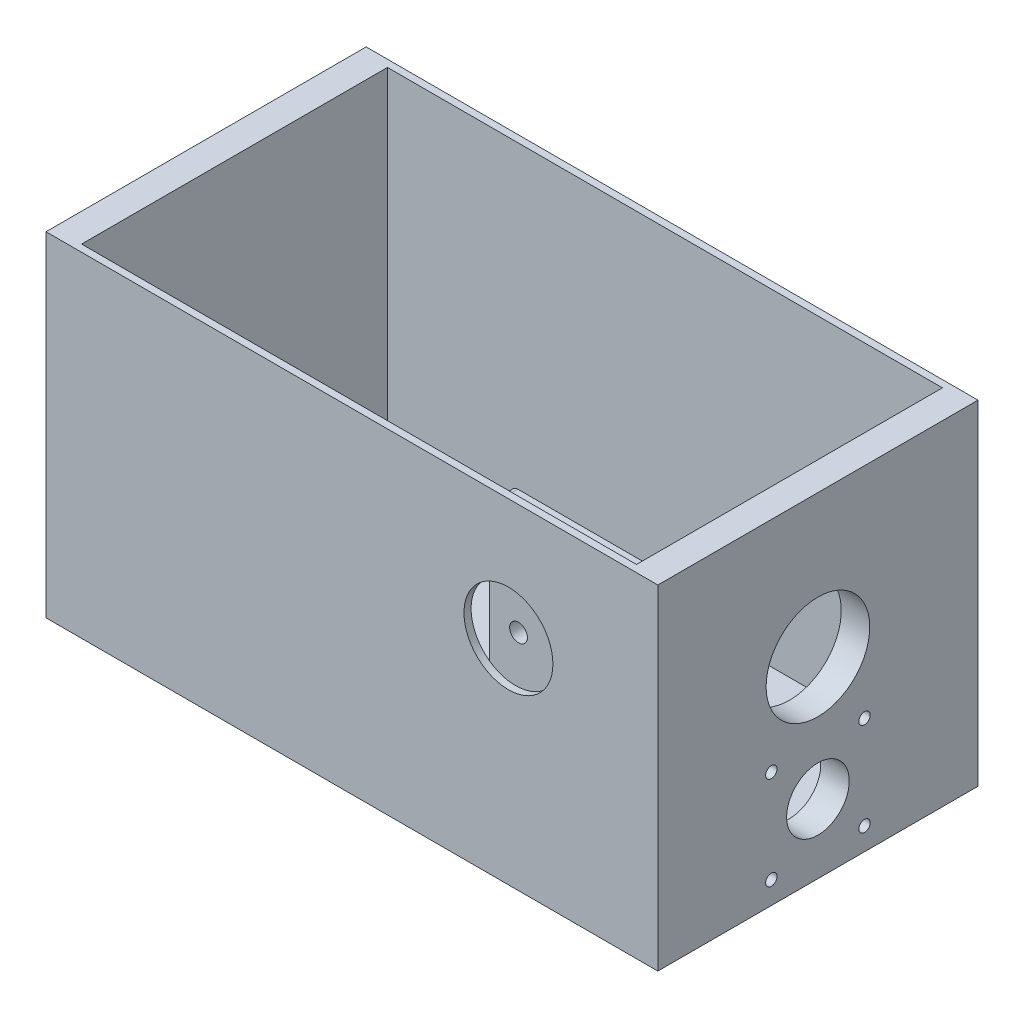
SolidWorks part; units mm, degrees
ref_plane "Front Plane" through (0, 0, 0) normal (0, 0, 1) x (1, 0, 0)
ref_plane "Top Plane" through (0, 0, 0) normal (0, 1, 0) x (1, 0, 0)
ref_plane "Right Plane" through (0, 0, 0) normal (1, 0, 0) x (0, 0, -1)
sketch "Sketch1" plane through (0, 0, 0) normal (0, 1, 0) x (1, 0, 0)
  line L1 (-101.6, -57.15) -> (101.6, -57.15)
  line L2 (-101.6, -57.15) -> (-101.6, 57.15)
  line L3 (-101.6, 57.15) -> (101.6, 57.15)
  line L4 (101.6, -57.15) -> (101.6, 57.15)
  line L5 (-101.6, -57.15) -> (101.6, 57.15) construction
  line L6 (-101.6, 57.15) -> (101.6, -57.15) construction
  point P0 (0, 0)
  dimension "10" = 203.2
  dimension "D2" = 114.3
extrude "Boss-Extrude1" add sketch "Sketch1" along normal blind 119.38
shell "Shell1" thickness 2.54
sketch "Sketch2" plane through (99.06, 0, 0) normal (-1, 0, 0) x (0, 0, 1)
  line L0 (22.225, 46.863) -> (-22.225, 46.863) construction
  line L5 (-22.225, 46.863) -> (-22.225, 2.413) construction
  line L10 (-22.225, 2.413) -> (22.225, 46.863) construction
  line L11 (-22.225, 46.863) -> (22.225, 2.413) construction
  line L12 (22.225, 46.863) -> (22.225, 2.413) construction
  line L14 (22.225, 2.413) -> (-22.225, 2.413) construction
  line L16 (0, 17.0459) -> (0, 33.3047) construction
  line L17 (1.822, 24.638) -> (-4.4847, 24.638) construction
  circle A0 centre (0, 68.58) radius 18.5
  circle A1 centre (16.637, 41.275) radius 2.032
  circle A5 centre (16.637, 8.001) radius 2.032
  circle A6 centre (-16.637, 8.001) radius 2.032
  circle A7 centre (-16.637, 41.275) radius 2.032
  circle A8 centre (0, 24.638) radius 11.176
  point P4 (0, 24.638)
  dimension "D3" = 37
  dimension "D4" = 4.064
  dimension "D5" = 33.274
  dimension "D6" = 22.352
  dimension "D1" = 44.45
  dimension "D2" = 44.45
extrude "Cut-Extrude1" cut sketch "Sketch2" against normal blind 2.54
sketch "Sketch3" plane through (101.6, 0, 0) normal (1, 0, 0) x (0, 0, -1)
  line L4 (-57.15, 0) -> (57.15, 0)
  line L5 (57.15, 0) -> (57.15, 119.38)
  line L6 (57.15, 119.38) -> (-57.15, 119.38)
  line L7 (-57.15, 119.38) -> (-57.15, 0)
  line L8 (-57.15, 0) -> (57.15, 0)
  line L9 (57.15, 0) -> (57.15, 119.38)
  line L10 (57.15, 119.38) -> (-57.15, 119.38)
  line L11 (-57.15, 119.38) -> (-57.15, 0)
  circle A0 centre (0, 68.58) radius 18.5 construction
  circle A1 centre (0, 68.58) radius 18.5
  circle A2 centre (-16.637, 8.001) radius 2.032 construction
  circle A3 centre (16.637, 8.001) radius 2.032 construction
  circle A4 centre (16.637, 41.275) radius 2.032 construction
  circle A5 centre (-16.637, 41.275) radius 2.032 construction
  circle A6 centre (-16.637, 8.001) radius 2.032
  circle A7 centre (16.637, 8.001) radius 2.032
  circle A8 centre (16.637, 41.275) radius 2.032
  circle A9 centre (-16.637, 41.275) radius 2.032
  circle A10 centre (0, 24.638) radius 11.176 construction
  circle A11 centre (0, 24.638) radius 11.176
  dimension "D1" = 0
extrude "Boss-Extrude3" add sketch "Sketch3" along normal blind 7.62
sketch "Sketch4" plane through (0, 0, 57.15) normal (0, 0, 1) x (1, 0, 0)
  line L1 (-101.6, 0) -> (109.22, 0) construction
  line L2 (109.22, 119.38) -> (109.22, 0) construction
  circle A0 centre (55.88, 76.2) radius 15.875
  dimension "D1" = 31.75
  dimension "D2" = 53.34
  dimension "D3" = 76.2
sketch "Sketch5" plane through (0, 2.54, 0) normal (0, 1, 0) x (1, 0, 0)
  line L5 (30.53, -38.55) -> (81.23, -38.55)
  line L6 (30.53, -38.55) -> (30.53, -30.93)
  line L7 (30.53, -30.93) -> (81.23, -30.93)
  line L8 (81.23, -38.55) -> (81.23, -30.93)
  line L9 (74.88, -38.55) -> (74.88, -39.95) construction
  dimension "D1" = 7.62
  dimension "D2" = 6.35
  dimension "D3" = 6.35
extrude "Cut-Extrude2" cut sketch "Sketch4" against normal blind 2.54
extrude "Boss-Extrude4" add sketch "Sketch5" along normal blind 95.25
sketch "Sketch6" plane through (0, 0, 38.55) normal (0, 0, 1) x (1, 0, 0)
  circle A1 centre (40.88, 91.2) radius 3.175
  circle A3 centre (70.88, 61.2) radius 3.175
  circle A4 centre (40.88, 61.2) radius 3.175
  circle A7 centre (70.88, 91.2) radius 3.175
  dimension "D1" = 6.35
  dimension "D2" = 6.35
  dimension "D3" = 6.35
  dimension "D4" = 6.35
extrude "Cut-Extrude3" cut sketch "Sketch6" against normal up to next
fillet "Fillet1" radius 2.54 2 edges at (30.53, 97.79, 34.74) (81.23, 97.79, 34.74)
fillet "Fillet2" radius 2.54 4 edges at (55.88, 2.54, 38.55) (81.23, 2.54, 34.74) (30.53, 2.54, 34.74) (55.88, 2.54, 30.93)
sketch "Sketch7" plane through (-101.6, 0, 0) normal (-1, 0, 0) x (0, 0, 1)
  line L4 (-57.15, 0) -> (57.15, 0)
  line L5 (57.15, 0) -> (57.15, 119.38)
  line L6 (57.15, 119.38) -> (-57.15, 119.38)
  line L7 (-57.15, 119.38) -> (-57.15, 0)
  line L8 (-57.15, 0) -> (57.15, 0)
  line L9 (57.15, 0) -> (57.15, 119.38)
  line L10 (57.15, 119.38) -> (-57.15, 119.38)
  line L11 (-57.15, 119.38) -> (-57.15, 0)
  dimension "D1" = 0
extrude "Boss-Extrude5" add sketch "Sketch7" along normal blind 7.62
sketch "Sketch8" plane through (0, 2.54, 0) normal (0, 1, 0) x (1, 0, 0)
  circle A2 centre (57.7271, -23.7315) radius 2.54
  circle A3 centre (59.4071, 34.2332) radius 2.54
  circle A4 centre (-26.4879, 34.2332) radius 2.54
  circle A5 centre (-28.2729, -23.7315) radius 2.54
  circle A6 centre (57.7271, -23.7315) radius 1.27
  circle A7 centre (59.4071, 34.2332) radius 1.27
  circle A8 centre (-26.4879, 34.2332) radius 1.27
  circle A9 centre (-28.2729, -23.7315) radius 1.27
  dimension "D1" = 5.08
  dimension "D2" = 5.08
  dimension "D3" = 5.08
  dimension "D4" = 5.08
  dimension "D5" = 2.54
  dimension "D6" = 2.54
  dimension "D7" = 2.54
  dimension "D8" = 2.54
extrude "Boss-Extrude6" add sketch "Sketch8" along normal blind 5.08
sketch "Sketch9" plane through (0, 0, -57.15) normal (0, 0, -1) x (-1, 0, 0)
  line L0 (-61.6571, 9.445) -> (-53.1571, 9.445) construction
  line L5 (-53.1571, 9.445) -> (-53.1571, 19.945) construction
  line L6 (-53.1571, 19.945) -> (-61.6571, 19.945) construction
  line L7 (-61.6571, 19.945) -> (-61.6571, 9.445) construction
  line L8 (-61.6571, 9.445) -> (-53.1571, 9.445) construction
  line L9 (-53.1571, 9.445) -> (-53.1571, 19.945) construction
  line L10 (-53.1571, 19.945) -> (-61.6571, 19.945) construction
  line L11 (-61.6571, 19.945) -> (-61.6571, 9.445) construction
  line L12 (-47.3071, 27.3712) -> (-32.0071, 27.3712)
  line L13 (-27.3571, 24.065) -> (-27.3571, 11.045) construction
  line L14 (-26.7571, 24.665) -> (-14.8571, 24.665) construction
  line L15 (-14.2571, 24.065) -> (-14.2571, 11.045) construction
  line L16 (-14.8571, 10.445) -> (-26.7571, 10.445) construction
  line L17 (-9.7571, 24.665) -> (2.1429, 24.665) construction
  line L18 (2.7429, 24.065) -> (2.7429, 11.045) construction
  line L19 (2.1429, 10.445) -> (-9.7571, 10.445) construction
  line L20 (-10.3571, 11.045) -> (-10.3571, 24.065) construction
  line L21 (-48.1071, 26.5712) -> (-48.1071, 10.1681)
  line L22 (-31.2134, 26.6712) -> (-31.2134, 10.107)
  line L23 (-47.8071, 9.8681) -> (-31.5071, 9.8681) construction
  line L24 (-47.8071, 9.8681) -> (-31.5071, 9.8681)
  line L25 (10.9129, 9.545) -> (15.9729, 9.545) construction
  line L26 (-62.6731, 8.429) -> (-52.1411, 8.429)
  line L27 (-52.1411, 8.429) -> (-52.1411, 20.961)
  line L28 (28.5729, 9.3212) -> (28.5729, 9.4912)
  line L29 (28.5729, 9.4912) -> (25.955, 9.4912)
  line L30 (25.7924, 9.5586) -> (25.1302, 10.2207)
  line L31 (25.0629, 10.3833) -> (25.0629, 11.2712)
  line L32 (25.2929, 11.5012) -> (31.8929, 11.5012)
  line L33 (32.1229, 11.2712) -> (32.1228, 10.3833)
  line L34 (32.0555, 10.2207) -> (31.3934, 9.5586)
  line L35 (31.2307, 9.4912) -> (28.6129, 9.4912)
  line L36 (28.6129, 9.4912) -> (28.6129, 9.3212)
  line L37 (28.6129, 9.3212) -> (31.2307, 9.3212)
  line L38 (31.5136, 9.4384) -> (32.1757, 10.1005)
  line L39 (32.2929, 10.3833) -> (32.2929, 11.2712)
  line L40 (31.8929, 11.6712) -> (25.2929, 11.6712)
  line L41 (24.8929, 11.2712) -> (24.8929, 10.3833)
  line L42 (25.01, 10.1005) -> (25.6721, 9.4384)
  line L43 (25.955, 9.3212) -> (28.5729, 9.3212)
  line L53 (28.6129, 9.3212) -> (31.2307, 9.3212) construction
  line L54 (31.5136, 9.4384) -> (32.1757, 10.1005) construction
  line L55 (32.2929, 10.3833) -> (32.2929, 11.2712) construction
  line L56 (31.8929, 11.6712) -> (25.2929, 11.6712) construction
  line L57 (24.8929, 11.2712) -> (24.8929, 10.3833) construction
  line L58 (25.01, 10.1005) -> (25.6721, 9.4384) construction
  line L59 (25.955, 9.3212) -> (28.5729, 9.3212) construction
  line L60 (-52.1411, 20.961) -> (-62.6731, 20.961)
  line L61 (-62.6731, 20.961) -> (-62.6731, 8.429)
  line L66 (-28.3731, 24.065) -> (-28.3731, 11.045)
  line L67 (-14.8571, 9.429) -> (-26.7571, 9.429)
  line L68 (6.9929, 12.5952) -> (6.9929, 14.885)
  line L69 (6.9929, 14.885) -> (6.9929, 16.885)
  line L70 (6.9929, 16.885) -> (6.9929, 20.265)
  line L71 (7.2428, 20.515) -> (19.6429, 20.515)
  line L72 (19.8928, 20.265) -> (19.8929, 16.885)
  line L73 (19.8929, 16.885) -> (19.8929, 14.8862)
  line L74 (19.8929, 14.8862) -> (19.8929, 12.5952)
  line L75 (19.8761, 12.505) -> (20.5929, 12.505)
  line L76 (20.5929, 12.505) -> (20.5929, 10.155)
  line L77 (20.5929, 10.155) -> (15.9729, 10.155)
  line L78 (15.9729, 10.155) -> (15.9729, 9.545)
  line L79 (15.9729, 9.545) -> (20.5429, 9.545)
  line L80 (20.5429, 9.545) -> (21.2928, 9.545)
  line L81 (21.2928, 9.545) -> (21.2929, 22.595)
  line L82 (21.2929, 22.595) -> (21.2929, 22.645)
  line L83 (21.2929, 22.645) -> (5.7929, 22.645)
  line L84 (5.7929, 22.645) -> (5.7929, 22.595)
  line L85 (5.7929, 22.595) -> (5.7929, 9.545)
  line L86 (5.7929, 9.545) -> (6.5429, 9.545)
  line L87 (6.5429, 9.545) -> (10.9129, 9.545)
  line L88 (10.9129, 9.545) -> (10.9129, 10.155)
  line L89 (10.9129, 10.155) -> (6.3929, 10.155)
  line L90 (6.3929, 10.155) -> (6.3929, 12.505)
  line L91 (6.3929, 12.505) -> (7.0096, 12.505)
  line L103 (15.9729, 9.545) -> (20.5429, 9.545) construction
  line L104 (20.5429, 9.545) -> (21.2928, 9.545) construction
  line L105 (21.2928, 9.545) -> (21.2929, 22.595) construction
  line L106 (21.2929, 22.595) -> (21.2929, 22.645) construction
  line L107 (21.2929, 22.645) -> (5.7929, 22.645) construction
  line L108 (5.7929, 22.645) -> (5.7929, 22.595) construction
  line L109 (5.7929, 22.595) -> (5.7929, 9.545) construction
  line L110 (5.7929, 9.545) -> (6.5429, 9.545) construction
  line L111 (6.5429, 9.545) -> (10.9129, 9.545) construction
  line L116 (-13.2411, 24.065) -> (-13.2411, 11.045)
  line L117 (-26.7571, 25.681) -> (-14.8571, 25.681)
  line L118 (-9.7571, 25.681) -> (2.1429, 25.681)
  line L119 (3.7589, 24.065) -> (3.7589, 11.045)
  line L120 (2.1429, 9.429) -> (-9.7571, 9.429)
  line L121 (-11.3731, 11.045) -> (-11.3731, 24.065)
  line L122 (10.9129, 8.529) -> (15.9729, 8.529)
  line L123 (15.9729, 8.529) -> (20.5429, 8.529)
  line L124 (20.5429, 8.529) -> (22.3088, 8.529)
  line L125 (22.3088, 8.529) -> (22.3089, 22.595)
  line L126 (22.3089, 22.595) -> (22.3089, 23.661)
  line L127 (22.3089, 23.661) -> (4.7769, 23.661)
  line L128 (4.7769, 23.661) -> (4.7769, 22.595)
  line L129 (4.7769, 22.595) -> (4.7769, 8.529)
  line L130 (4.7769, 8.529) -> (6.5429, 8.529)
  line L131 (6.5429, 8.529) -> (10.9129, 8.529)
  line L132 (28.6129, 8.3052) -> (31.2307, 8.3052)
  line L133 (32.232, 8.7199) -> (32.8941, 9.3821)
  line L134 (33.3089, 10.3833) -> (33.3089, 11.2712)
  line L135 (31.8929, 12.6872) -> (25.2929, 12.6872)
  line L136 (23.8769, 11.2712) -> (23.8769, 10.3833)
  line L137 (24.2916, 9.3821) -> (24.9537, 8.7199)
  line L138 (25.955, 8.3052) -> (28.5729, 8.3052)
  line L139 (-47.0911, 26.3552) -> (-32.2294, 26.3552) construction
  line L140 (-47.0911, 26.3552) -> (-47.0911, 10.8841) construction
  line L141 (-32.2294, 26.3552) -> (-32.2294, 10.107) construction
  line L142 (-47.0911, 10.8841) -> (-31.928, 10.8841) construction
  arc A1 (-47.3071, 27.3712) -> (-48.1071, 26.5712) centre (-47.3071, 26.5712) ccw construction
  arc A2 (6.9929, 12.5952) -> (7.0096, 12.505) centre (7.2437, 12.5952) ccw
  arc A3 (7.2428, 20.515) -> (6.9929, 20.265) centre (7.2428, 20.265) ccw
  arc A4 (19.8928, 20.265) -> (19.6429, 20.515) centre (19.6429, 20.265) ccw
  arc A5 (19.8761, 12.505) -> (19.8929, 12.5952) centre (19.642, 12.5952) ccw
  arc A10 (-31.2134, 26.6712) -> (-32.0071, 27.3712) centre (-32.0071, 26.5712) ccw construction
  arc A11 (-26.7571, 24.665) -> (-27.3571, 24.065) centre (-26.7571, 24.065) ccw construction
  arc A12 (25.7924, 9.5586) -> (25.955, 9.4912) centre (25.955, 9.7212) ccw
  arc A13 (25.0629, 10.3833) -> (25.1302, 10.2207) centre (25.2929, 10.3833) ccw
  arc A14 (25.2929, 11.5012) -> (25.0629, 11.2712) centre (25.2929, 11.2712) ccw
  arc A15 (32.1229, 11.2712) -> (31.8929, 11.5012) centre (31.8929, 11.2712) ccw
  arc A16 (32.0555, 10.2207) -> (32.1228, 10.3833) centre (31.8929, 10.3833) ccw
  arc A17 (31.2307, 9.4912) -> (31.3934, 9.5586) centre (31.2307, 9.7212) ccw
  arc A18 (31.2307, 9.3212) -> (31.5136, 9.4384) centre (31.2307, 9.7212) ccw
  arc A19 (32.1757, 10.1005) -> (32.2929, 10.3833) centre (31.8929, 10.3833) ccw
  arc A20 (32.2929, 11.2712) -> (31.8929, 11.6712) centre (31.8929, 11.2712) ccw
  arc A21 (25.2929, 11.6712) -> (24.8929, 11.2712) centre (25.2929, 11.2712) ccw
  arc A22 (24.8929, 10.3833) -> (25.01, 10.1005) centre (25.2929, 10.3833) ccw
  arc A23 (25.6721, 9.4384) -> (25.955, 9.3212) centre (25.955, 9.7212) ccw
  arc A30 (31.2307, 9.3212) -> (31.5136, 9.4384) centre (31.2307, 9.7212) ccw construction
  arc A31 (32.1757, 10.1005) -> (32.2929, 10.3833) centre (31.8929, 10.3833) ccw construction
  arc A32 (32.2929, 11.2712) -> (31.8929, 11.6712) centre (31.8929, 11.2712) ccw construction
  arc A33 (25.2929, 11.6712) -> (24.8929, 11.2712) centre (25.2929, 11.2712) ccw construction
  arc A34 (24.8929, 10.3833) -> (25.01, 10.1005) centre (25.2929, 10.3833) ccw construction
  arc A35 (25.6721, 9.4384) -> (25.955, 9.3212) centre (25.955, 9.7212) ccw construction
  arc A36 (-27.3571, 11.045) -> (-26.7571, 10.445) centre (-26.7571, 11.045) ccw construction
  arc A37 (-14.8571, 10.445) -> (-14.2571, 11.045) centre (-14.8571, 11.045) ccw construction
  arc A38 (-10.3571, 11.045) -> (-9.7571, 10.445) centre (-9.7571, 11.045) ccw construction
  arc A39 (2.1429, 10.445) -> (2.7429, 11.045) centre (2.1429, 11.045) ccw construction
  arc A40 (2.7429, 24.065) -> (2.1429, 24.665) centre (2.1429, 24.065) ccw construction
  arc A41 (-9.7571, 24.665) -> (-10.3571, 24.065) centre (-9.7571, 24.065) ccw construction
  arc A42 (-14.2571, 24.065) -> (-14.8571, 24.665) centre (-14.8571, 24.065) ccw construction
  arc A43 (-48.1071, 10.1681) -> (-47.8071, 9.8681) centre (-47.8071, 10.1681) ccw construction
  arc A44 (-47.3071, 27.3712) -> (-48.1071, 26.5712) centre (-47.3071, 26.5712) ccw
  arc A45 (-31.2134, 26.6712) -> (-32.0071, 27.3712) centre (-32.0071, 26.5712) ccw
  arc A46 (-26.7571, 24.665) -> (-27.3571, 24.065) centre (-26.7571, 24.065) ccw construction
  arc A47 (-27.3571, 11.045) -> (-26.7571, 10.445) centre (-26.7571, 11.045) ccw construction
  arc A48 (-14.8571, 10.445) -> (-14.2571, 11.045) centre (-14.8571, 11.045) ccw construction
  arc A49 (-10.3571, 11.045) -> (-9.7571, 10.445) centre (-9.7571, 11.045) ccw construction
  arc A50 (2.1429, 10.445) -> (2.7429, 11.045) centre (2.1429, 11.045) ccw construction
  arc A51 (2.7429, 24.065) -> (2.1429, 24.665) centre (2.1429, 24.065) ccw construction
  arc A52 (-9.7571, 24.665) -> (-10.3571, 24.065) centre (-9.7571, 24.065) ccw construction
  arc A53 (-14.2571, 24.065) -> (-14.8571, 24.665) centre (-14.8571, 24.065) ccw construction
  arc A54 (-48.1071, 10.1681) -> (-47.8071, 9.8681) centre (-47.8071, 10.1681) ccw
  arc A55 (-31.5071, 9.8681) -> (-31.2071, 10.1681) centre (-31.5071, 10.1681) ccw construction
  arc A56 (-31.5071, 9.8681) -> (-31.2071, 10.1681) centre (-31.5071, 10.1681) ccw
  arc A57 (-31.928, 10.8841) -> (-31.928, 10.8841) centre (-31.928, 10.8841) cw
  arc A58 (-47.0911, 10.8841) -> (-47.0911, 10.8841) centre (-47.0911, 10.8841) ccw
  arc A59 (-47.0911, 26.3552) -> (-47.0911, 26.3552) centre (-47.0911, 26.3552) ccw
  arc A60 (-32.2294, 26.3552) -> (-32.2294, 26.3552) centre (-32.2294, 26.3552) ccw
  arc A61 (-28.3731, 11.045) -> (-26.7571, 9.429) centre (-26.7571, 11.045) ccw
  arc A62 (-14.8571, 9.429) -> (-13.2411, 11.045) centre (-14.8571, 11.045) ccw
  arc A63 (-13.2411, 24.065) -> (-14.8571, 25.681) centre (-14.8571, 24.065) ccw
  arc A64 (-26.7571, 25.681) -> (-28.3731, 24.065) centre (-26.7571, 24.065) ccw
  arc A65 (3.7589, 24.065) -> (2.1429, 25.681) centre (2.1429, 24.065) ccw
  arc A66 (2.1429, 9.429) -> (3.7589, 11.045) centre (2.1429, 11.045) ccw
  arc A67 (-11.3731, 11.045) -> (-9.7571, 9.429) centre (-9.7571, 11.045) ccw
  arc A68 (-9.7571, 25.681) -> (-11.3731, 24.065) centre (-9.7571, 24.065) ccw
  arc A69 (31.2307, 8.3052) -> (32.232, 8.7199) centre (31.2307, 9.7212) ccw
  arc A70 (32.8941, 9.3821) -> (33.3089, 10.3833) centre (31.8929, 10.3833) ccw
  arc A71 (33.3089, 11.2712) -> (31.8929, 12.6872) centre (31.8929, 11.2712) ccw
  arc A72 (25.2929, 12.6872) -> (23.8769, 11.2712) centre (25.2929, 11.2712) ccw
  arc A73 (23.8769, 10.3833) -> (24.2916, 9.3821) centre (25.2929, 10.3833) ccw
  arc A74 (24.9537, 8.7199) -> (25.955, 8.3052) centre (25.955, 9.7212) ccw
  dimension "D1" = 0
  dimension "D2" = 0
  dimension "D3" = 1.016
